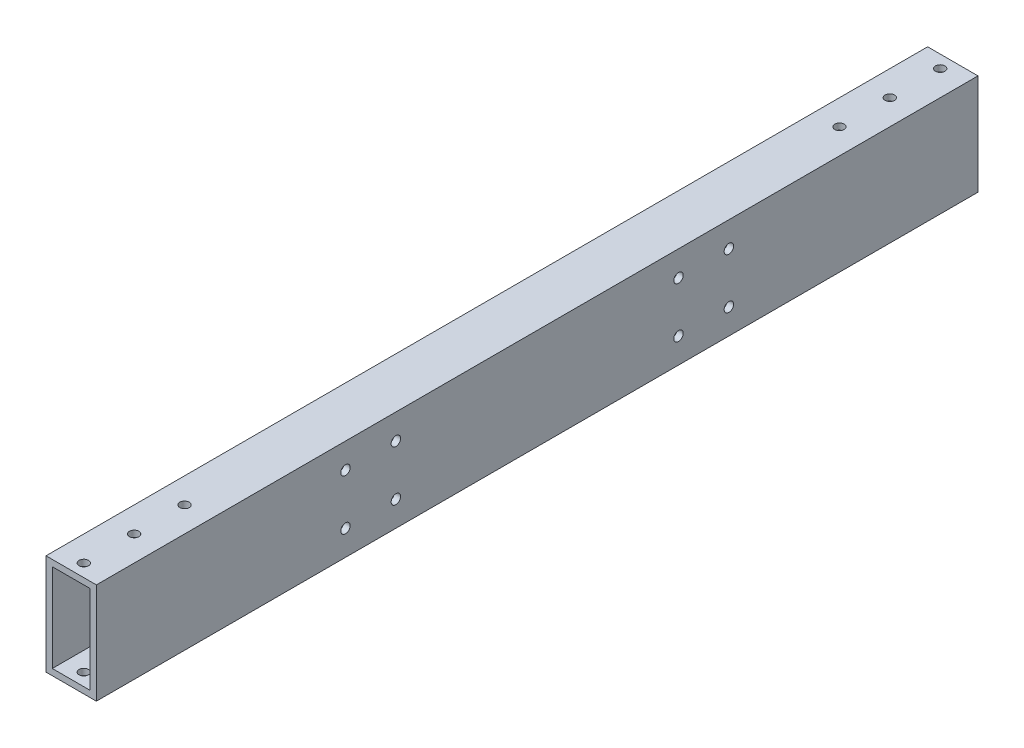
SolidWorks part; units mm, degrees
material "6063-T1"
ref_plane "Front Plane" through (0, 0, 0) normal (0, 0, 1) x (1, 0, 0)
ref_plane "Top Plane" through (0, 0, 0) normal (0, 1, 0) x (1, 0, 0)
ref_plane "Right Plane" through (0, 0, 0) normal (1, 0, 0) x (0, 0, -1)
sketch "Sketch1" plane through (0, 0, 0) normal (0, 0, 1) x (1, 0, 0)
  line L1 (-12.7, 25.4) -> (12.7, 25.4)
  line L2 (-12.7, 25.4) -> (-12.7, -25.4)
  line L3 (-12.7, -25.4) -> (12.7, -25.4)
  line L4 (12.7, 25.4) -> (12.7, -25.4)
  line L5 (-12.7, 25.4) -> (12.7, -25.4) construction
  line L6 (-12.7, -25.4) -> (12.7, 25.4) construction
  point P0 (0, 0)
  dimension "D1" = 25.4
  dimension "D2" = 50.8
extrude "Boss-Extrude1" add sketch "Sketch1" along normal blind 444.5
shell "Shell1" thickness 3.175
sketch "Sketch2" plane through (0, 25.4, 0) normal (0, 1, 0) x (1, 0, 0)
  line L0 (12.7, 0) -> (-12.7, 0) construction
  line L1 (12.7, -222.25) -> (-14.2289, -222.25) construction
  line L2 (12.7, -444.5) -> (12.7, 0) construction
  circle A0 centre (0, -6.35) radius 2.3812
  circle A3 centre (0, -31.75) radius 2.3812
  circle A4 centre (0, -57.15) radius 2.3812
  circle A5 centre (0, -387.35) radius 2.3812
  circle A6 centre (0, -412.75) radius 2.3812
  circle A7 centre (0, -438.15) radius 2.3813
  dimension "D1" = 4.7625
  dimension "D2" = 6.35
  dimension "D3" = 3
extrude "Cut-Extrude1" cut sketch "Sketch2" against normal through all
sketch "Sketch3" plane through (12.7, 0, 0) normal (1, 0, 0) x (0, 0, -1)
  line L0 (0, -25.4) -> (0, 25.4) construction
  line L1 (-444.5, -25.4) -> (0, -25.4) construction
  line L2 (-222.25, 25.4) -> (-222.25, -26.5117) construction
  line L3 (-444.5, 25.4) -> (0, 25.4) construction
  circle A0 centre (-125.603, -12.7) radius 2.3813
  circle A1 centre (-125.603, 12.7) radius 2.3813
  circle A2 centre (-151.003, 12.7) radius 2.3813
  circle A3 centre (-151.003, -12.7) radius 2.3813
  circle A4 centre (-293.497, -12.7) radius 2.3812
  circle A5 centre (-293.497, 12.7) radius 2.3813
  circle A6 centre (-318.897, 12.7) radius 2.3812
  circle A7 centre (-318.897, -12.7) radius 2.3813
  dimension "D4" = 4.7625
  dimension "D5" = 4.7625
  dimension "D8" = 4.7625
  dimension "D9" = 4.7625
  dimension "D1" = 125.603
  dimension "D2" = 25.4
  dimension "D3" = 12.7
  dimension "D6" = 25.4
  dimension "D7" = 25.4
extrude "Cut-Extrude2" cut sketch "Sketch3" against normal blind 6.35
